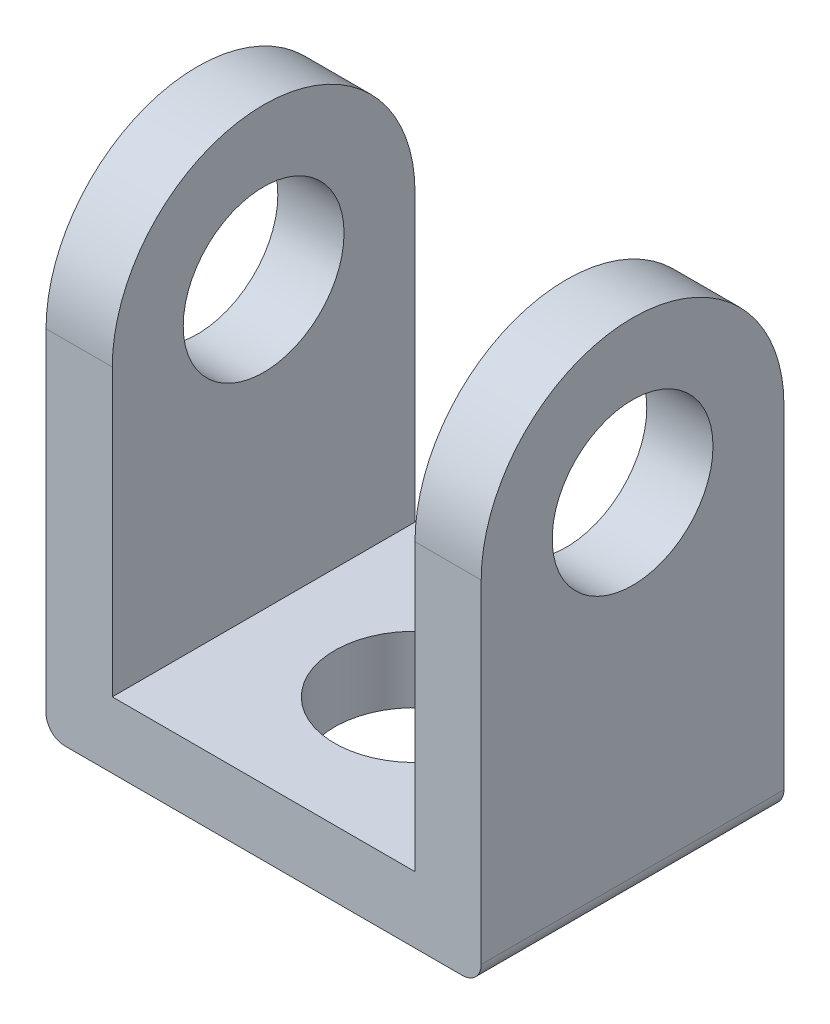
SolidWorks part; units mm, degrees
ref_plane "Front Plane" through (0, 0, 0) normal (0, 0, 1) x (1, 0, 0)
ref_plane "Top Plane" through (0, 0, 0) normal (0, 1, 0) x (1, 0, 0)
ref_plane "Right Plane" through (0, 0, 0) normal (1, 0, 0) x (0, 0, -1)
sketch "Sketch1" plane through (0, 0, 0) normal (0, 1, 0) x (1, 0, 0)
  line L0 (-5.75, -4) -> (5.75, -4)
  line L1 (-5.75, -4) -> (-5.75, 4)
  line L2 (5.75, -4) -> (5.75, 4)
  line L3 (-5.75, 4) -> (5.75, 4)
  line L4 (-5.75, -4) -> (5.75, 4) construction
  line L5 (5.75, -4) -> (-5.75, 4) construction
  point P1 (0, 0)
  dimension "D1" = 11.5
  dimension "D2" = 8
extrude "Boss-Extrude1" add sketch "Sketch1" along normal blind 13.3
sketch "Sketch2" plane through (5.75, 0, 0) normal (1, 0, 0) x (0, 0, -1)
  line L0 (-4, 0) -> (4, 0) construction
  circle A0 centre (0, 9.3) radius 2.125
  point P2 (0, 0)
  dimension "D2" = 4.25
  dimension "D1" = 9.3
extrude "Cut-Extrude1" cut sketch "Sketch2" against normal up to next
sketch "Sketch3" plane through (5.75, 0, 0) normal (1, 0, 0) x (0, 0, -1)
  line L0 (-4, 13.3) -> (-4, 0) construction
  line L1 (-4, 13.3) -> (4, 13.3) construction
  line L2 (4, 13.3) -> (4, 0) construction
  line L3 (-4, 13.3) -> (-4, 9.3)
  line L4 (-4, 13.3) -> (4, 13.3)
  line L5 (4, 13.3) -> (4, 9.3)
  circle A2 centre (0, 9.3) radius 4
  arc A3 (4, 9.3) -> (-4, 9.3) centre (0, 9.3) ccw
  line M4 (4, 0) -> (4, 13.3)
  line M5 (4, 13.3) -> (-4, 13.3)
  line M6 (-4, 13.3) -> (-4, 0)
  dimension "D1" = 1.875
extrude "Cut-Extrude2" cut sketch "Sketch3" against normal up to next contours A3 M4 M5 | A3 L4 M6
sketch "Sketch4" plane through (0, 0, 4) normal (0, 0, 1) x (1, 0, 0)
  line L8 (5.75, 13.3) -> (-5.75, 13.3) construction
  line L9 (4, 13.3) -> (-4, 13.3)
  line L11 (-4, 9.3) -> (-4, 1.75)
  line L12 (4, 1.75) -> (4, 9.3)
  line L13 (-4, 1.75) -> (4, 1.75)
  line L14 (-4, 13.3) -> (-4, 1.75)
  line L15 (4, 1.75) -> (4, 13.3)
  line L16 (-4, 1.75) -> (4, 1.75)
  dimension "D1" = 1.75
extrude "Cut-Extrude3" cut sketch "Sketch4" against normal up to next
sketch "Sketch5" plane through (0, 0, 0) normal (0, -1, 0) x (1, 0, 0)
  circle A0 centre (0, 0) radius 2.125
extrude "Cut-Extrude4" cut sketch "Sketch5" against normal up to next
fillet "Fillet1" radius 0.5 2 edges at (5.75, 0, 0) (-5.75, 0, 0)
